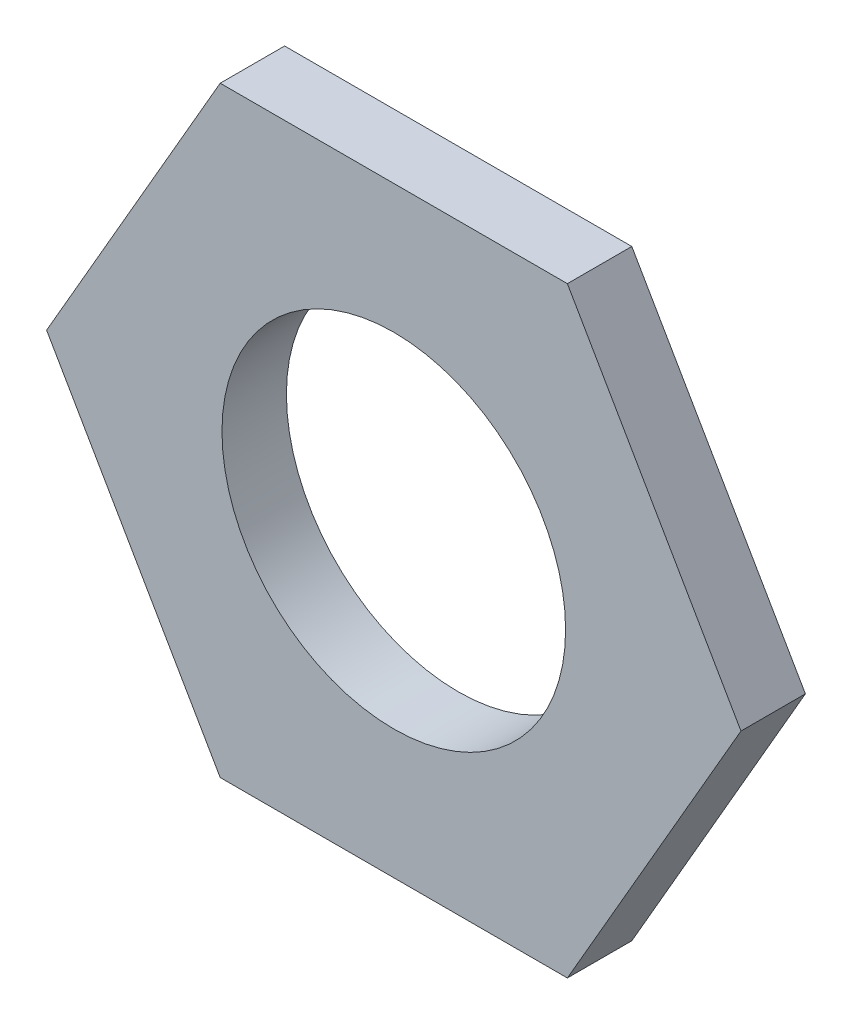
SolidWorks part; units mm, degrees
ref_plane "Front Plane" through (0, 0, 0) normal (0, 0, 1) x (1, 0, 0)
ref_plane "Top Plane" through (0, 0, 0) normal (0, 1, 0) x (1, 0, 0)
ref_plane "Right Plane" through (0, 0, 0) normal (1, 0, 0) x (0, 0, -1)
sketch "Sketch1" plane through (0, 0, 0) normal (0, 0, 1) x (1, 0, 0)
  line L0 (77.182, -94.0483) -> (-39.998, -94.0483) construction
  line L1 (47.1405, -68.9744) -> (55.2234, -68.9744)
  line L2 (55.2234, -68.9744) -> (59.2649, -61.9744)
  line L3 (59.2649, -61.9744) -> (55.2234, -54.9744)
  line L4 (55.2234, -54.9744) -> (47.1405, -54.9744)
  line L5 (47.1405, -54.9744) -> (43.0991, -61.9744)
  line L6 (43.0991, -61.9744) -> (47.1405, -68.9744)
  circle A0 centre (51.182, -61.9744) radius 7 construction
  circle A1 centre (51.182, -61.9744) radius 4
  circle A2 centre (51.182, -61.9744) radius 15.7 construction
  dimension "D1" = 8
  dimension "D2" = 14
extrude "Boss-Extrude1" add sketch "Sketch1" along normal blind 1.5
